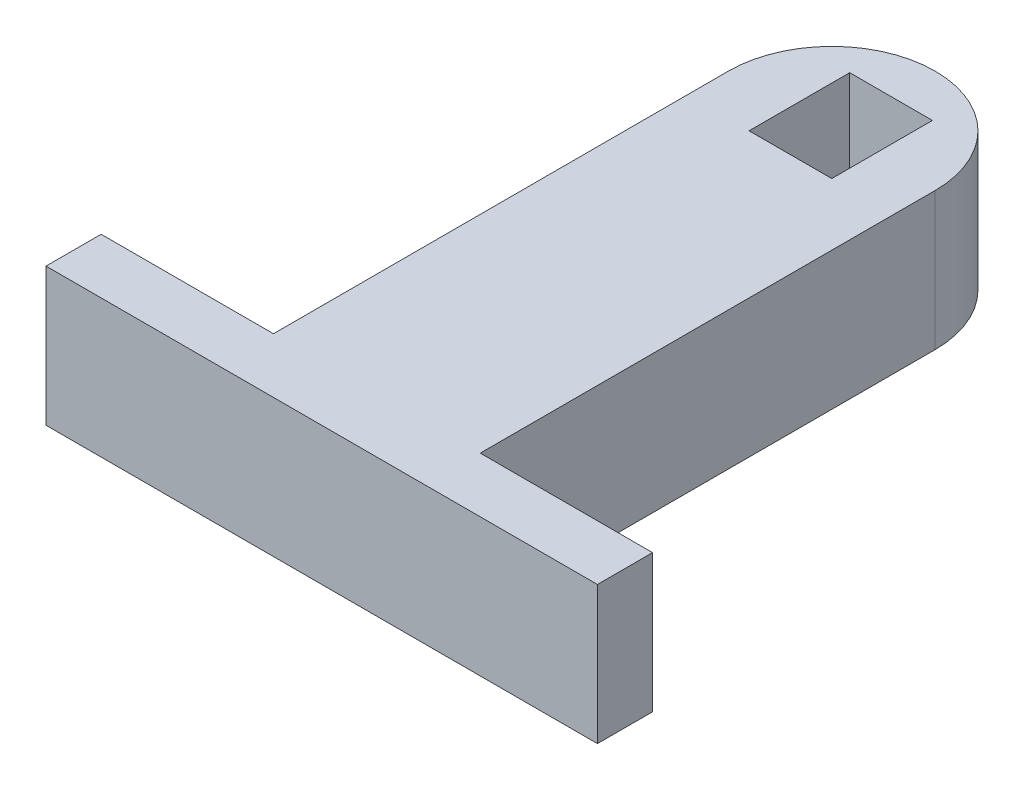
SolidWorks part; units mm, degrees
ref_plane "Alzado" through (0, 0, 0) normal (0, 0, 1) x (1, 0, 0)
ref_plane "Planta" through (0, 0, 0) normal (0, 1, 0) x (1, 0, 0)
ref_plane "Vista lateral" through (0, 0, 0) normal (1, 0, 0) x (0, 0, -1)
sketch "Croquis2" plane through (0, 0, 0) normal (0, 1, 0) x (1, 0, 0)
  line L0 (-275, 40) -> (-275, 345)
  line L1 (0, 0) -> (-400, 0)
  line L2 (0, 0) -> (0, 40)
  line L3 (0, 40) -> (-400, 40)
  line L4 (-400, 0) -> (-400, 40)
  line L5 (-200, 40) -> (-125, 40)
  line L8 (-125, 40) -> (-125, 345)
  line L9 (-125, 370) -> (-125, 345)
  line L10 (-275, 370) -> (-275, 345)
  circle A0 centre (-200, 370) radius 25
  circle A1 centre (-200, 370) radius 75
extrude "Saliente-Extruir1" add sketch "Croquis2" along normal blind 100 contours A1 A0 | A1 L10 L0 L3 L8 L9 | L4 L1 L2 L3
sketch "Croquis3" plane through (0, 0, 0) normal (0, -1, 0) x (1, 0, 0)
  line L3 (-170, -413) -> (-230, -413)
  line L8 (-170, -413) -> (-170, -340)
  line L9 (-170, -340) -> (-230, -340)
  line L10 (-230, -413) -> (-230, -340)
extrude "Cortar-Extruir1" cut sketch "Croquis3" against normal blind 107
